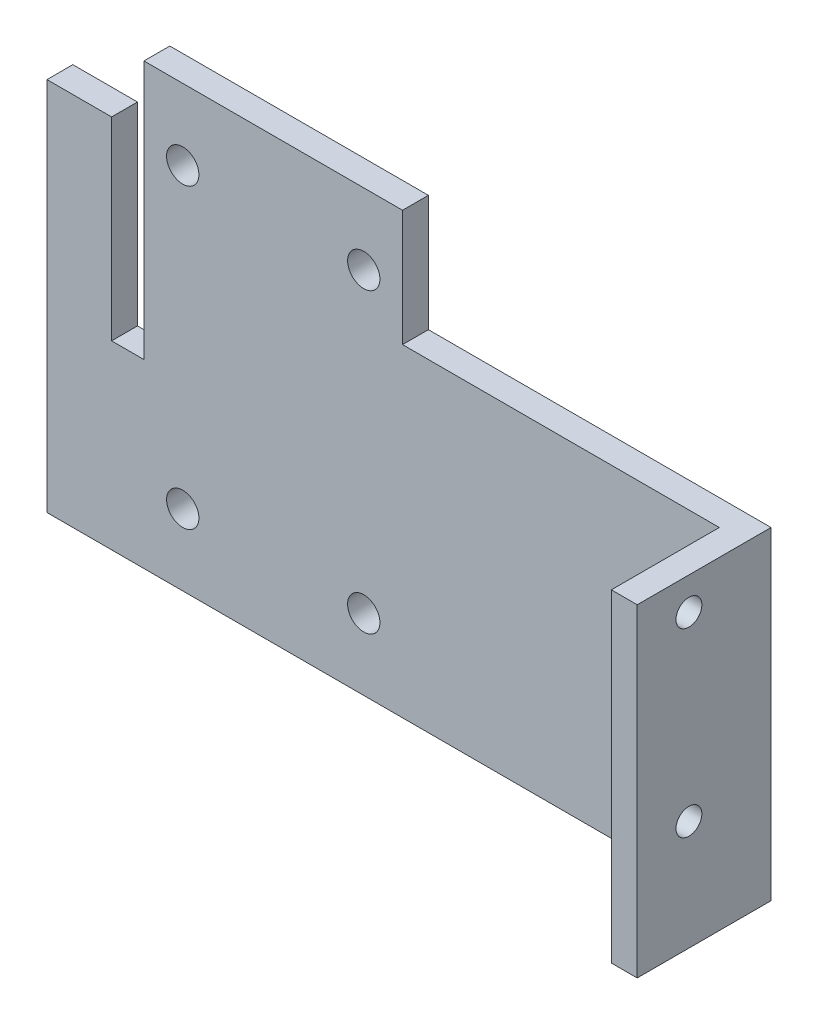
SolidWorks part; units mm, degrees
ref_plane "Спереди" through (0, 0, 0) normal (0, 0, 1) x (1, 0, 0)
ref_plane "Сверху" through (0, 0, 0) normal (0, 1, 0) x (1, 0, 0)
ref_plane "Справа" through (0, 0, 0) normal (1, 0, 0) x (0, 0, -1)
sketch "Эскиз1" plane through (0, 0, 0) normal (0, 0, 1) x (1, 0, 0)
  line L0 (35, 68) -> (35, 0) construction
  line L1 (0, 0) -> (108, 0)
  line L2 (0, 0) -> (0, 68)
  line L3 (0, 68) -> (55, 68)
  line L4 (108, 0) -> (108, 50)
  line L5 (21, 68) -> (21, 0) construction
  line L6 (55, 68) -> (55, 50)
  line L7 (55, 50) -> (108, 50)
  line L8 (49, 68) -> (49, 0) construction
  circle A0 centre (21, 57) radius 2.5
  circle A1 centre (49, 57) radius 2.5
  circle A2 centre (21, 11) radius 2.5
  circle A3 centre (49, 11) radius 2.5
  circle A4 centre (93, 25) radius 2.5
  dimension "D8" = 5
  dimension "D9" = 5
  dimension "D10" = 5
  dimension "D11" = 5
  dimension "D18" = 5
  dimension "D1" = 108
  dimension "D2" = 68
  dimension "D3" = 55
  dimension "D4" = 50
  dimension "D5" = 35
  dimension "D6" = 14
  dimension "D7" = 14
  dimension "D12" = 46
  dimension "D13" = 46
  dimension "D14" = 11
  dimension "D15" = 11
  dimension "D16" = 15
  dimension "D17" = 25
extrude "Бобышка-Вытянуть1" add sketch "Эскиз1" along normal blind 4
sketch "Эскиз2" plane through (0, 0, 4) normal (0, 0, 1) x (1, 0, 0)
  line L0 (0, 0) -> (108, 0) construction
  line L1 (108, 50) -> (104, 50)
  line L2 (108, 50) -> (108, 0)
  line L3 (108, 0) -> (104, 0)
  line L4 (104, 50) -> (104, 0)
  dimension "D1" = 4
extrude "Бобышка-Вытянуть2" add sketch "Эскиз2" along normal blind 16.7
sketch "Эскиз3" plane through (108, 0, 0) normal (1, 0, 0) x (0, 0, -1)
  line L0 (-12.7, 50) -> (-12.7, 0) construction
  line L1 (-20.7, 50) -> (0, 50) construction
  line L2 (-20.7, 0) -> (0, 0) construction
  line L3 (-20.7, 0) -> (-20.7, 50) construction
  circle A0 centre (-12.7, 45) radius 2
  circle A1 centre (-12.7, 17) radius 2
  dimension "D2" = 4
  dimension "D3" = 4
  dimension "D1" = 8
  dimension "D4" = 5
  dimension "D5" = 28
extrude "Вырез-Вытянуть1" cut sketch "Эскиз3" against normal blind 10
sketch "Эскиз4" plane through (0, 0, 4) normal (0, 0, 1) x (1, 0, 0)
  line L1 (0, 68) -> (15, 68)
  line L2 (0, 68) -> (0, 58)
  line L3 (0, 58) -> (10, 58)
  line L4 (15, 68) -> (15, 58)
  line L6 (15, 58) -> (15, 28)
  line L7 (15, 28) -> (10, 28)
  line L8 (10, 58) -> (10, 28)
  dimension "D1" = 15
  dimension "D2" = 10
  dimension "D3" = 40
  dimension "D4" = 5
extrude "Вырез-Вытянуть2" cut sketch "Эскиз4" against normal blind 10
